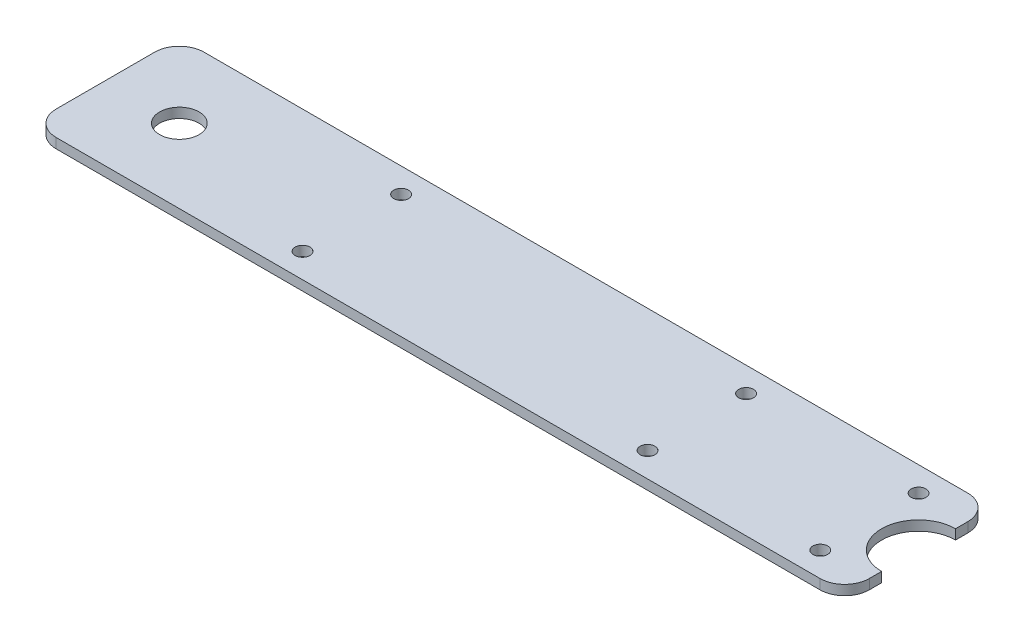
SolidWorks part; units mm, degrees
ref_plane "Front Plane" through (0, 0, 0) normal (0, 0, 1) x (1, 0, 0)
ref_plane "Top Plane" through (0, 0, 0) normal (0, 1, 0) x (1, 0, 0)
ref_plane "Right Plane" through (0, 0, 0) normal (1, 0, 0) x (0, 0, -1)
sketch "Sketch1" plane through (0, 0, 0) normal (0, 1, 0) x (1, 0, 0)
  line L1 (-82.5, 15) -> (82.5, 15)
  line L2 (-82.5, 15) -> (-82.5, -15)
  line L3 (-82.5, -15) -> (82.5, -15)
  line L4 (82.5, 15) -> (82.5, -15)
  line L5 (-82.5, 15) -> (82.5, -15) construction
  line L6 (-82.5, -15) -> (82.5, 15) construction
  point P0 (0, 0)
  dimension "D1" = 165
  dimension "D2" = 30
extrude "Boss-Extrude1" add sketch "Sketch1" along normal blind 2
fillet "Fillet1" radius 5 4 edges at (82.5, 1, 15) (82.5, 1, -15) (-82.5, 1, -15) (-82.5, 1, 15)
sketch "Sketch3" plane through (0, 2, 0) normal (0, 1, 0) x (1, 0, 0)
  line L1 (-67.5, 6) -> (-67.5, -28.9997) construction
  line L3 (-67.5, 0) -> (-62.3038, -3) construction
  line L4 (-67.5, 0) -> (-72.6962, -3) construction
  circle A0 centre (-67.5, 0) radius 4
  point P9 (-67.5, 0)
  point P16 (-61.0048, -3.75)
  point P17 (-73.9952, -3.75)
  dimension "D2" = 8
extrude "Cut-Extrude1" cut sketch "Sketch3" against normal blind 2
sketch "Sketch4" plane through (0, 2, 0) normal (0, 1, 0) x (1, 0, 0)
  line L0 (91.6385, 0) -> (59.0764, 0) construction
  line L1 (82.5, -10) -> (82.5, 10) construction
  circle A0 centre (82.5, 0) radius 7.5
  dimension "D1" = 15
extrude "Cut-Extrude2" cut sketch "Sketch4" against normal blind 10
sketch "Sketch5" plane through (0, 2, 0) normal (0, 1, 0) x (1, 0, 0)
  line L0 (-59.4849, 10) -> (68.8081, 10) construction
  line L1 (77.5, 15) -> (-77.5, 15) construction
  line L2 (-59.4849, -10) -> (68.8081, -10) construction
  line L3 (-77.5, -15) -> (77.5, -15) construction
  line L4 (-82.5, 10) -> (-82.5, -10) construction
  circle A0 centre (-32.5, 10) radius 1.5
  circle A1 centre (37.5, 10) radius 1.5
  circle A2 centre (-32.5, -10) radius 1.5
  circle A3 centre (37.5, -10) radius 1.5
  dimension "D3" = 3
  dimension "D1" = 5
  dimension "D2" = 5
  dimension "D4" = 50
  dimension "D5" = 50
  dimension "D6" = 120
  dimension "D7" = 120
extrude "Cut-Extrude3" cut sketch "Sketch5" against normal blind 10
sketch "Sketch6" plane through (0, 2, 0) normal (0, 1, 0) x (1, 0, 0)
  line L0 (72.5, 15) -> (72.5, -15) construction
  line L1 (77.5, 15) -> (-77.5, 15) construction
  line L2 (-77.5, -15) -> (77.5, -15) construction
  line L3 (82.5, -10) -> (82.5, -7.5) construction
  line L4 (58.504, 10) -> (77.6656, 10) construction
  line L5 (64.3802, -10) -> (80.7315, -10) construction
  circle A0 centre (72.5, 10) radius 1.5
  circle A1 centre (72.5559, -10) radius 1.5
  point P11 (82.5, -8.75)
  point P13 (68.0848, 10)
  point P14 (72.5, 10)
  point P15 (72.5, -10)
  point P16 (72.5, 10)
  dimension "D4" = 3
  dimension "D5" = 3
  dimension "D1" = 10
  dimension "D2" = 5
  dimension "D3" = 5
extrude "Cut-Extrude4" cut sketch "Sketch6" against normal through all
